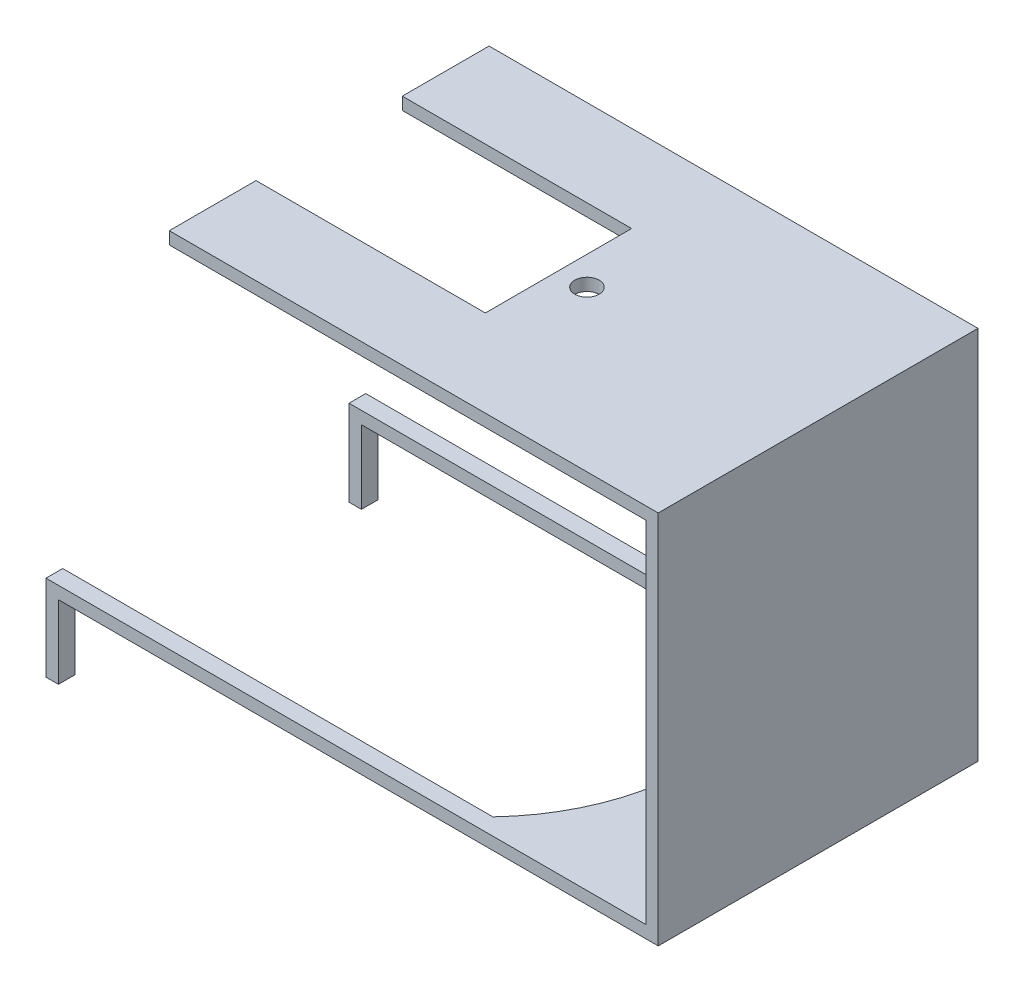
SolidWorks part; units mm, degrees
ref_plane "Alzado" through (0, 0, 0) normal (0, 0, 1) x (1, 0, 0)
ref_plane "Planta" through (0, 0, 0) normal (0, 1, 0) x (1, 0, 0)
ref_plane "Vista lateral" through (0, 0, 0) normal (1, 0, 0) x (0, 0, -1)
sketch "Croquis1" plane through (0, 0, 0) normal (0, 0, 1) x (1, 0, 0)
  line L0 (-15.3647, -0.5287) -> (-15.3647, -1.5287)
  line L1 (-15.3647, -1.5287) -> (23.0849, -1.5287)
  line L2 (23.0849, -1.5287) -> (23.0849, -29.7835)
  line L3 (23.0849, -29.7835) -> (-25.3109, -29.7835)
  line L4 (-25.3109, -29.7835) -> (-25.3109, -36.7018)
  line L5 (-25.3109, -36.7018) -> (-24.3109, -36.7018)
  line L6 (-24.3109, -36.7018) -> (-24.3109, -30.7835)
  line L7 (-24.3109, -30.7835) -> (24.0849, -30.7835)
  line L8 (24.0849, -30.7835) -> (24.0849, -0.5287)
  line L9 (24.0849, -0.5287) -> (-15.3647, -0.5287)
  spline S0 degree 3 poles (-12.0525, -51.024) (-10.9091, -52.1509) (-10.288, -52.6523) (-9.2826, -53.312) (-8.9374, -53.5147) (-8.2338, -53.8828) (-7.5152, -54.215) (-6.7665, -54.4762) (-6.0026, -54.7011) (-5.611, -54.7958) (-4.4356, -55.019) (-3.6471, -55.0895) (-2.0608, -55.0766) (-1.2562, -54.9906) (0.2971, -54.6676) (1.0528, -54.4319) (2.1542, -53.9652) (2.517, -53.7899) (3.2161, -53.4084) (3.8926, -52.9948) (4.5247, -52.5181) (5.1344, -52.0096) (5.4289, -51.7384) (6.2714, -50.8816) (6.7685, -50.2643) (7.4204, -49.2713) (7.622, -48.9291) (7.9929, -48.2217) (8.1618, -47.8565) (8.609, -46.7504) (8.8324, -45.9913) (9.0558, -44.8202) (9.1117, -44.4223) (9.1834, -43.6259) (9.1994, -43.2288) (9.1895, -42.0406) (9.1062, -41.2527) (8.8627, -40.0773) (8.7619, -39.6889) (8.5249, -38.9306) (8.2519, -38.1872) (7.9076, -37.4733) (7.5271, -36.7744) (7.3173, -36.4306) (6.6439, -35.4405) (6.1364, -34.8328) (5.289, -33.9983) (4.992, -33.7331) (4.3682, -33.2293) (4.0453, -32.994) (3.0501, -32.3407) (2.3493, -31.9729) (1.2414, -31.5238) (0.8609, -31.391) (0.0964, -31.1658) (-0.2891, -31.0727) (-1.4553, -30.8503) (-2.247, -30.7776) (-3.8507, -30.7901) (-4.6391, -30.8749) (-5.802, -31.1154) (-6.1864, -31.2147) (-6.9484, -31.4521) (-7.3265, -31.5907) (-8.4257, -32.0564) (-9.1206, -32.4349) (-10.1064, -33.1042) (-10.4269, -33.3455) (-11.0416, -33.8581) (-11.334, -34.1275) (-12.1677, -34.9746) (-12.666, -35.5902) (-13.3249, -36.5923) (-13.5287, -36.9387) (-13.8978, -37.6426) (-14.2308, -38.3613) (-14.4923, -39.1093) (-14.7176, -39.872) (-14.8126, -40.263) (-15.0372, -41.44) (-15.1083, -42.2287) (-15.0996, -43.4176) (-15.0774, -43.8149) (-14.993, -44.6115) (-14.931, -45.0071) (-14.6896, -46.1734) (-14.4545, -46.9291) (-13.9895, -48.0294) (-13.8145, -48.3924) (-13.4332, -49.0929) (-13.2265, -49.4316) (-12.5594, -50.4139) (-12.0525, -51.024) (-10.9091, -52.1509) (-10.288, -52.6523) knots -0.03125 -0.03125 0 0 0.03125 0.03125 0.046875 0.046875 0.0625 0.078125 0.078125 0.09375 0.09375 0.125 0.125 0.15625 0.15625 0.1875 0.1875 0.203125 0.203125 0.21875 0.234375 0.234375 0.25 0.25 0.28125 0.28125 0.296875 0.296875 0.3125 0.3125 0.34375 0.34375 0.359375 0.359375 0.375 0.375 0.40625 0.40625 0.421875 0.421875 0.4375 0.453125 0.453125 0.46875 0.46875 0.5 0.5 0.515625 0.515625 0.53125 0.53125 0.5625 0.5625 0.578125 0.578125 0.59375 0.59375 0.625 0.625 0.65625 0.65625 0.671875 0.671875 0.6875 0.6875 0.71875 0.71875 0.734375 0.734375 0.75 0.75 0.78125 0.78125 0.796875 0.796875 0.8125 0.828125 0.828125 0.84375 0.84375 0.875 0.875 0.890625 0.890625 0.90625 0.90625 0.9375 0.9375 0.953125 0.953125 0.96875 0.96875 1 1 1.03125 1.03125 1.046875 only from (-11.4808, -51.5874) to (-11.4808, -51.5874) construction
  dimension "D2" = 1
  dimension "D3" = 1
  dimension "D4" = 1
  dimension "D5" = 1
extrude "Saliente-Extruir1" add sketch "Croquis1" along normal blind 25.8
sketch "Croquis2" plane through (0, -0.5287, 0) normal (0, 1, 0) x (1, 0, 0)
  line L1 (-15.3647, -12.9) -> (24.0849, -12.9) construction
  line L2 (-15.3647, -25.8) -> (-15.3647, 0) construction
  line L3 (24.0849, -25.8) -> (24.0849, 0) construction
  line L4 (3.1353, -18.8) -> (3.1353, -7)
  line L5 (3.1353, -7) -> (-15.3647, -7)
  line L6 (-15.3647, -7) -> (-15.3647, -18.8)
  line L7 (-15.3647, -18.8) -> (3.1353, -18.8)
  circle A0 centre (5.4353, -12.9) radius 0.9863
  dimension "D1" = 18.5
  dimension "D2" = 5.9
  dimension "D3" = 11.8
  dimension "D4" = 2.3
extrude "Cortar-Extruir1" cut sketch "Croquis2" against normal up to surface (1 mm away)
sketch "Croquis3" plane through (0, -29.7835, 0) normal (0, 1, 0) x (1, 0, 0)
  line L0 (-25.3109, -1.35) -> (9.3914, -1.35)
  line L1 (-25.3109, -25.8) -> (-25.3109, 0) construction
  line L2 (-25.3109, -24.45) -> (-25.3109, -1.35)
  line L3 (9.3914, -24.45) -> (-25.3109, -24.45)
  arc A0 (9.3914, -24.45) -> (9.3914, -1.35) centre (-2.7809, -12.9) ccw
  dimension "D5" = 33.56
extrude "Cortar-Extruir2" cut sketch "Croquis3" against normal through all
